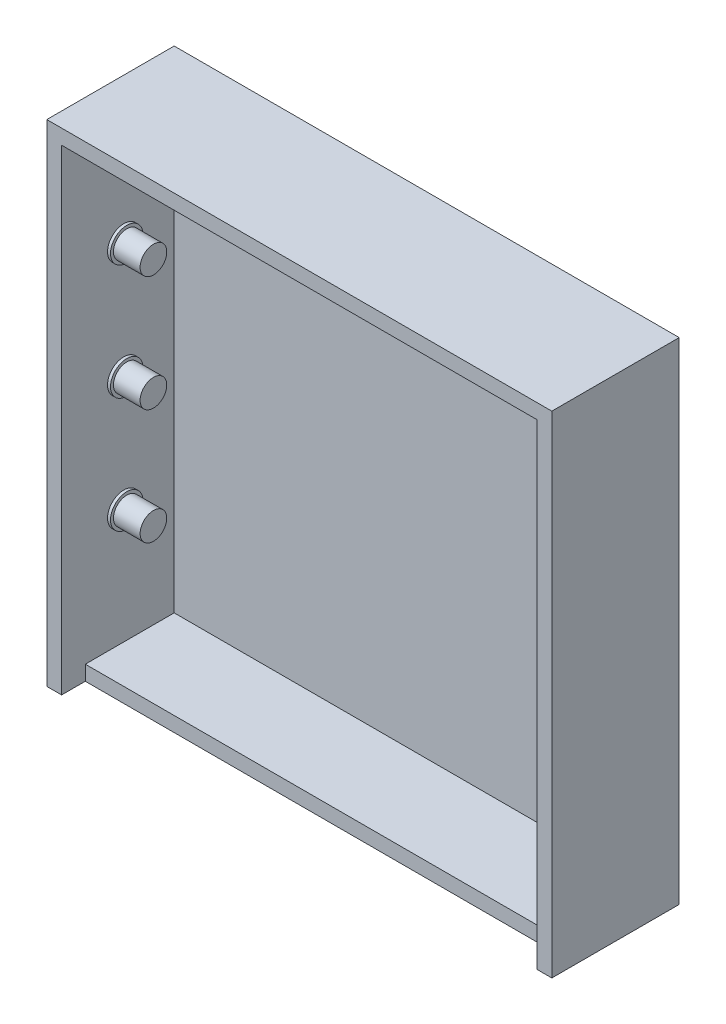
SolidWorks part; units mm, degrees
ref_plane "Front Plane" through (0, 0, 0) normal (0, 0, 1) x (1, 0, 0)
ref_plane "Top Plane" through (0, 0, 0) normal (0, 1, 0) x (1, 0, 0)
ref_plane "Right Plane" through (0, 0, 0) normal (1, 0, 0) x (0, 0, -1)
sketch "Sketch1" plane through (0, 0, 0) normal (0, 0, 1) x (1, 0, 0)
  line L1 (0, 0) -> (170.47, 0)
  line L2 (0, 0) -> (0, 165.71)
  line L3 (0, 165.71) -> (170.47, 165.71)
  line L4 (170.47, 0) -> (170.47, 165.71)
  dimension "D1" = 165.71
  dimension "D2" = 170.47
extrude "Boss-Extrude1" add sketch "Sketch1" along normal blind 5
sketch "Sketch2" plane through (0, 0, 5) normal (0, 0, 1) x (1, 0, 0)
  line L0 (0, 0) -> (0, 165.71)
  line L1 (0, 165.71) -> (170.47, 165.71)
  line L2 (170.47, 165.71) -> (170.47, 0)
  line L3 (170.47, 0) -> (0, 0)
  line L4 (5, 160.71) -> (5, 5)
  line L5 (5, 5) -> (165.47, 5)
  line L6 (165.47, 5) -> (165.47, 160.71)
  line L7 (165.47, 160.71) -> (5, 160.71)
  dimension "D1" = 5
  dimension "D2" = 5
  dimension "D3" = 5
  dimension "D4" = 5
extrude "Boss-Extrude2" add sketch "Sketch2" along normal blind 38
sketch "Sketch3" plane through (0, 0, 43) normal (0, 0, 1) x (1, 0, 0)
  line L0 (5, 5) -> (165.47, 5) construction
  line L1 (5, 5) -> (165.47, 5)
  line L2 (5, 5) -> (5, 0)
  line L3 (5, 0) -> (165.47, 0)
  line L4 (165.47, 5) -> (165.47, 0)
  line L5 (0, 0) -> (170.47, 0) construction
  line L6 (0, 165.71) -> (0, 0) construction
  dimension "D1" = 160.47
  dimension "D2" = 5
extrude "Cut-Extrude1" cut sketch "Sketch3" against normal blind 8
sketch "Sketch5" plane through (165.47, 0, 0) normal (-1, 0, 0) x (0, 0, 1)
  line L0 (43, 160.71) -> (5, 160.71) construction
  line L1 (43, 0) -> (43, 160.71) construction
  circle A0 centre (22, 121.7825) radius 5.5
  dimension "D1" = 11
  dimension "D2" = 38.9275
  dimension "D3" = 21
extrude "Boss-Extrude3" add sketch "Sketch5" along normal blind 1
sketch "Sketch6" plane through (164.47, 0, 0) normal (-1, 0, 0) x (0, 0, 1)
  circle A0 centre (22, 121.7825) radius 4.5
  dimension "D1" = 9
extrude "Boss-Extrude4" add sketch "Sketch6" along normal blind 9
ref_plane "Plane1" through (85.235, 0, 0) normal (-1, 0, 0) x (0, 0, 1)
pattern_linear "LPattern1" count 3 spacing 38.9275 along (0, -1, 0) of "Boss-Extrude4", "Boss-Extrude3"
mirror "Mirror1" about plane through (85.235, 0, 0) normal (-1, 0, 0) of "LPattern1", "Boss-Extrude3", "Boss-Extrude4"
